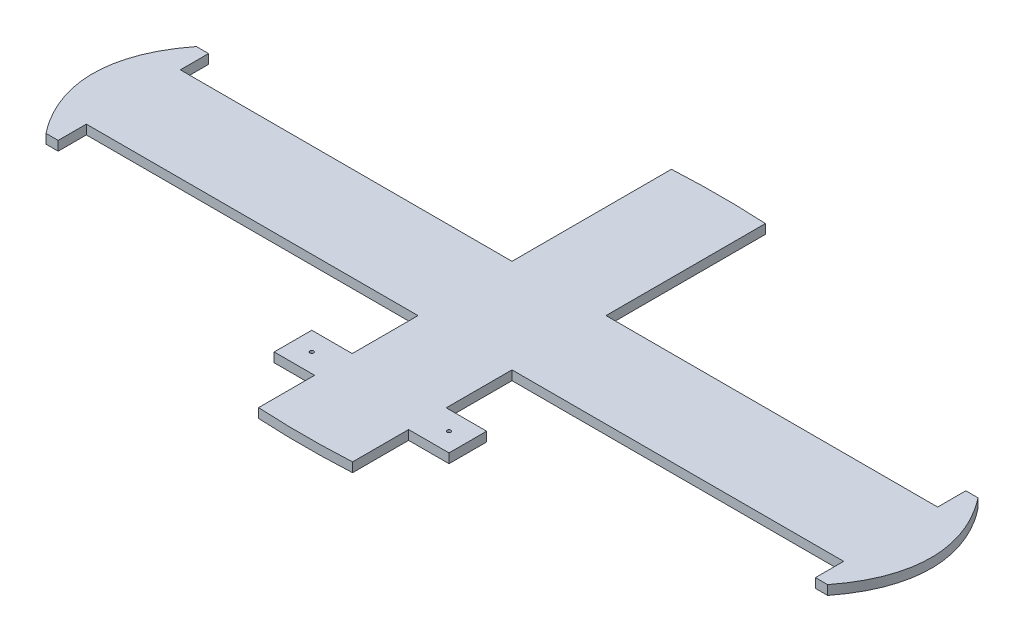
SolidWorks part; units mm, degrees
ref_plane "Front Plane" through (0, 0, 0) normal (0, 0, 1) x (1, 0, 0)
ref_plane "Top Plane" through (0, 0, 0) normal (0, 1, 0) x (1, 0, 0)
ref_plane "Right Plane" through (0, 0, 0) normal (1, 0, 0) x (0, 0, -1)
sketch "Sketch1" plane through (0, 0, 0) normal (0, 1, 0) x (1, 0, 0)
  line L0 (25, 25) -> (201.4092, 25)
  line L13 (-201.4092, 40) -> (-201.4092, 25)
  line L14 (201.4092, 40) -> (201.4092, 25)
  line L17 (-207.8765, -40) -> (-201.4092, -40)
  line L18 (25, -25) -> (25, -109.8034)
  line L21 (-25, -25) -> (-25, -109.8034)
  line L22 (-25, -109.8034) -> (-25, -25)
  line L23 (25, 25) -> (25, 109.8034)
  line L24 (-25, 25) -> (-201.4092, 25)
  line L25 (-201.4092, 25) -> (-25, 25)
  line L26 (0, 0) -> (0, 40) construction
  line L27 (25, -25) -> (201.4092, -25)
  line L28 (201.4092, -25) -> (25, -25)
  line L29 (-201.4092, 40) -> (-207.8765, 40)
  line L30 (-207.8765, 40) -> (-201.4092, 40)
  line L31 (201.4092, 40) -> (207.8765, 40)
  line L32 (201.4092, -40) -> (207.8765, -40)
  line L33 (-201.4092, -40) -> (-207.8765, -40)
  line L34 (201.4092, -25) -> (201.4092, -40)
  line L35 (-25, -25) -> (-201.4092, -25)
  line L36 (-25, 25) -> (-25, 109.8034)
  line L37 (-201.4092, -25) -> (-201.4092, -40)
  ellipse E0 centre (0, 0) end of major axis (-223, 0) minor radius 110.5 (207.8765, -40) -> (207.8765, 40) ccw
  ellipse E1 centre (0, 0) end of major axis (-223, 0) minor radius 110.5 (-25, -109.8034) -> (25, -109.8034) ccw
  ellipse E2 centre (0, 0) end of major axis (-223, 0) minor radius 110.5 (-207.8765, 40) -> (-207.8765, -40) ccw
  ellipse E3 centre (0, 0) end of major axis (-223, 0) minor radius 110.5 (25, 109.8034) -> (-25, 109.8034) ccw
  dimension "D1" = 446
  dimension "D2" = 221
  dimension "D5" = 50
  dimension "D3" = 50
  dimension "D9" = 40
extrude "Boss-Extrude1" add sketch "Sketch1" along normal blind 5
sketch "Sketch3" plane through (0, 5, 0) normal (0, 1, 0) x (1, 0, 0)
  line L0 (0, 0) -> (0, -70)
  line L1 (0, -70) -> (36.5, -70) construction
  line L2 (0, -70) -> (-36.5, -70) construction
  line L3 (-36.5, -70) -> (-36.5, -60)
  line L4 (-36.5, -60) -> (-46.5, -60)
  line L5 (-46.5, -60) -> (-46.5, -80)
  line L6 (-46.5, -80) -> (46.5, -80)
  line L7 (46.5, -80) -> (46.5, -60)
  line L8 (46.5, -60) -> (-36.5, -60)
  circle A0 centre (-36.5, -70) radius 1
  circle A1 centre (36.5, -70) radius 1
  dimension "D3" = 2
  dimension "D4" = 2
  dimension "D1" = 36.5
  dimension "D2" = 36.5
  dimension "D5" = 10
  dimension "D6" = 10
  dimension "D7" = 10
  dimension "D8" = 10
  dimension "D9" = 70
extrude "Boss-Extrude2" add sketch "Sketch3" against normal blind 5
